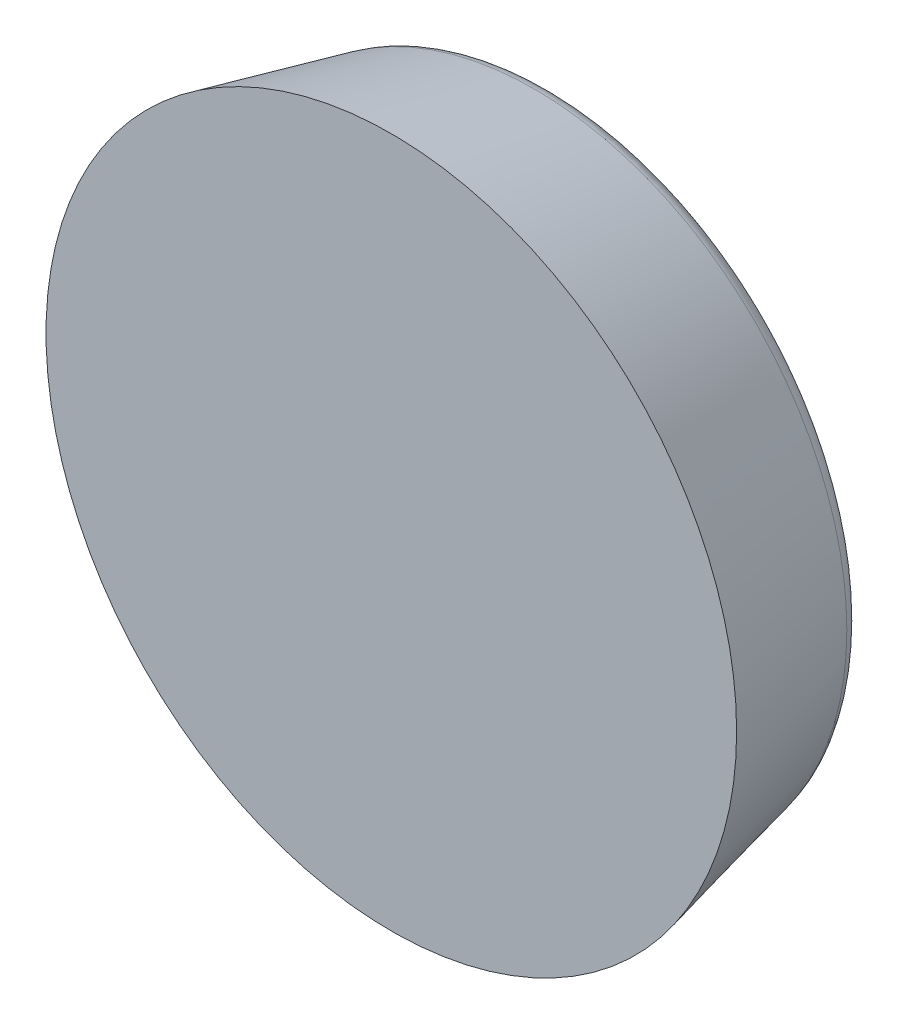
SolidWorks part; units mm, degrees
ref_plane "Alzado" through (0, 0, 0) normal (0, 0, 1) x (1, 0, 0)
ref_plane "Planta" through (0, 0, 0) normal (0, 1, 0) x (1, 0, 0)
ref_plane "Vista lateral" through (0, 0, 0) normal (1, 0, 0) x (0, 0, -1)
sketch "Croquis1" plane through (0, 0, 0) normal (0, 0, 1) x (1, 0, 0)
  circle A0 centre (0, 0) radius 15
  dimension "D1" = 30
extrude "Saliente-Extruir1" add sketch "Croquis1" against normal blind 7 draft 13 contours A0
sketch "Croquis3" plane through (0, 0, -7) normal (0, 0, -1) x (-1, 0, 0)
  circle A0 centre (0, 0) radius 10
  dimension "D1" = 20
extrude "Cortar-Extruir1" cut sketch "Croquis3" against normal blind 3
fillet "Redondeo4" radius 1 1 edges at (-10, 0, -7)
fillet "Redondeo5" radius 1 1 edges at (13.3839, 0, -7)
sketch "Croquis4" plane through (0, 0, -4) normal (0, 0, -1) x (-1, 0, 0)
  line L0 (6.1847, 2) -> (8.5, 2)
  line L1 (-8.5, -2) -> (-6.1847, -2)
  line L2 (-8.5, -2) -> (-8.5, 2)
  line L3 (-8.5, 2) -> (-6.1847, 2)
  line L4 (8.5, -2) -> (8.5, 2)
  line L9 (6.1847, -2) -> (8.5, -2)
  arc A0 (6.1847, 2) -> (-6.1847, 2) centre (0, 0) ccw
  circle A1 centre (0, 0) radius 2
  arc A2 (-6.1847, -2) -> (6.1847, -2) centre (0, 0) ccw
  dimension "D1" = 13
  dimension "D2" = 4
  dimension "D3" = 4
  dimension "D4" = 17
  dimension "D5" = 2.3153
extrude "Cortar-Extruir3" cut sketch "Croquis4" against normal blind 3.5 contours L0 L4 L9 A2 L1 L2 L3 A0 | A1
